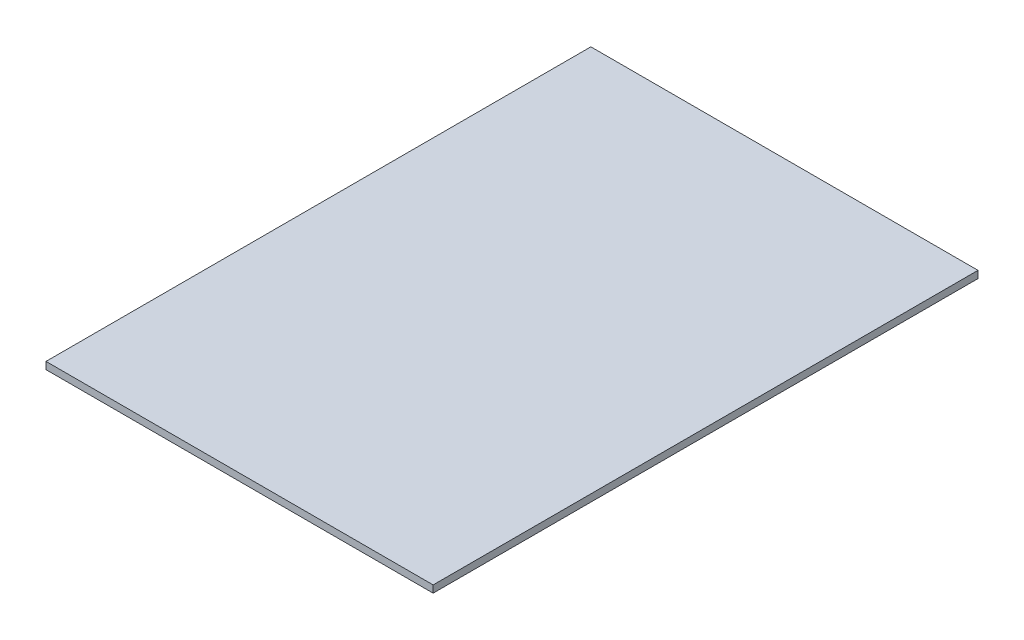
SolidWorks part; units mm, degrees
material "2024-T361"
ref_plane "Front Plane" through (0, 0, 0) normal (0, 0, 1) x (1, 0, 0)
ref_plane "Top Plane" through (0, 0, 0) normal (0, 1, 0) x (1, 0, 0)
ref_plane "Right Plane" through (0, 0, 0) normal (1, 0, 0) x (0, 0, -1)
sketch "Sketch1" plane through (0, 0, 0) normal (0, 0, 1) x (1, 0, 0)
  line L0 (5, -60) -> (5, 85) construction
  line L1 (5, 45) -> (275, 45)
  line L2 (5, 45) -> (5, 50)
  line L3 (5, 50) -> (275, 50)
  line L4 (275, 45) -> (275, 50)
  line L5 (275, -60) -> (275, 85) construction
  line L7 (3, -65) -> (277, -65) construction
  dimension "D1" = 5
  dimension "D2" = 110
extrude "Boss-Extrude1" add sketch "Sketch1" along normal blind 380
